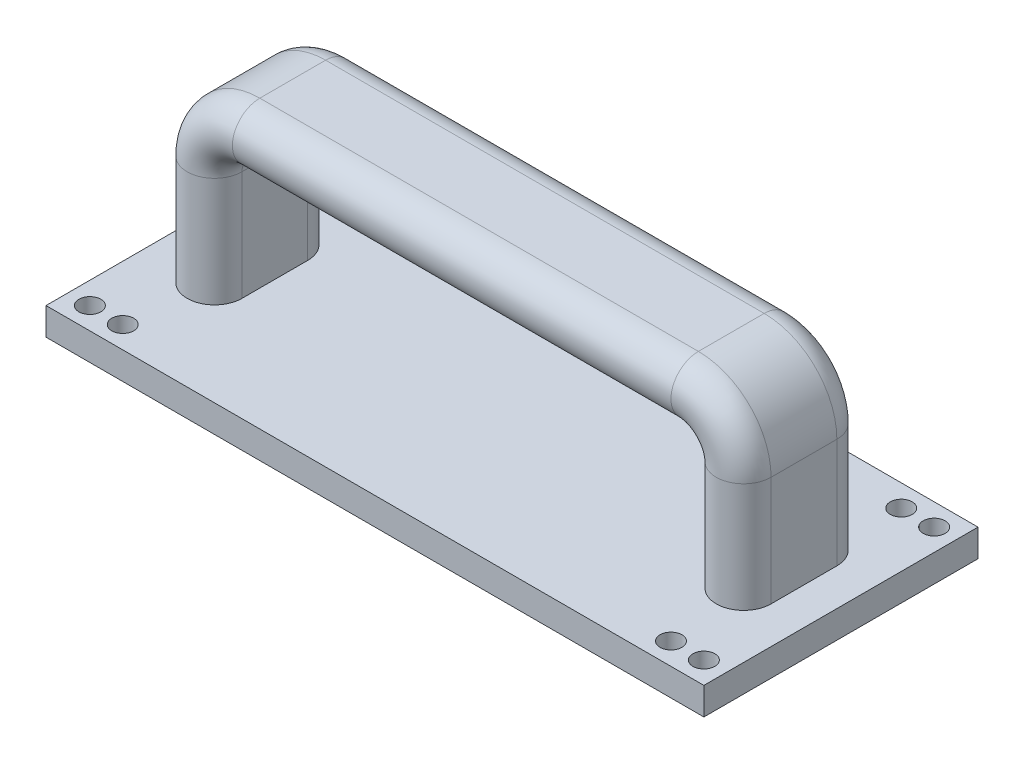
SolidWorks part; units mm, degrees
ref_plane "Front Plane" through (0, 0, 0) normal (0, 0, 1) x (1, 0, 0)
ref_plane "Top Plane" through (0, 0, 0) normal (0, 1, 0) x (1, 0, 0)
ref_plane "Right Plane" through (0, 0, 0) normal (1, 0, 0) x (0, 0, -1)
sketch "Sketch3" plane through (0, 0, 0) normal (0, 1, 0) x (1, 0, 0)
  line L1 (-60, -25) -> (60, -25)
  line L2 (-60, -25) -> (-60, 25)
  line L3 (-60, 25) -> (60, 25)
  line L4 (60, -25) -> (60, 25)
  line L5 (-60, -25) -> (60, 25) construction
  line L6 (-60, 25) -> (60, -25) construction
  point P0 (0, 0)
  dimension "D1" = 120
  dimension "D2" = 50
extrude "Boss-Extrude1" add sketch "Sketch3" along normal blind 5
sketch "Sketch4" plane through (0, 0, 0) normal (0, 0, 1) x (1, 0, 0)
  line L0 (-50, 5) -> (-50, 25)
  line L1 (-60, 5) -> (60, 5) construction
  line L2 (-40, 35) -> (40, 35)
  line L3 (0, 65.4422) -> (0, -12.7136) construction
  line L4 (50, 5) -> (50, 25)
  arc A0 (-50, 25) -> (-40, 35) centre (-40, 25) cw
  arc A1 (50, 25) -> (40, 35) centre (40, 25) ccw
  point P13 (0, 35)
  dimension "D1" = 10
  dimension "D2" = 30
  dimension "D3" = 100
sketch "Sketch5" plane through (0, 5, 0) normal (0, 1, 0) x (1, 0, 0)
  line L1 (-60, 0) -> (0, 0) construction
  line L3 (-60, 25) -> (-60, -25) construction
  line L4 (-40, 0) -> (40, 0) construction
  line L5 (-48.2577, 6) -> (-48.2577, -6) construction
  line L6 (-43.2577, 6) -> (-43.2577, -6)
  line L7 (-53.2577, 6) -> (-53.2577, -6)
  arc A1 (-43.2577, 6) -> (-53.2577, 6) centre (-48.2577, 6) ccw
  arc A2 (-53.2577, -6) -> (-43.2577, -6) centre (-48.2577, -6) ccw
  point P8 (-48.2577, 0)
  dimension "D1" = 10
sweep "Sweep1" add profiles "Sketch5" path "Sketch4"
sketch "Sketch6" plane through (0, 5, 0) normal (0, 1, 0) x (1, 0, 0)
  line L0 (60, 25) -> (-60, 25) construction
  line L1 (-60, 25) -> (-60, -25) construction
  line L2 (0, 0) -> (-60, 0) construction
  line L3 (0, 25) -> (0, -25) construction
  line L4 (-60, -25) -> (60, -25) construction
  circle A0 centre (-56, 21) radius 2
  circle A1 centre (-50, 21) radius 2
  circle A2 centre (-50, -21) radius 2
  circle A3 centre (-56, -21) radius 2
  circle A4 centre (56, -21) radius 2
  circle A5 centre (50, -21) radius 2
  circle A6 centre (50, 21) radius 2
  circle A7 centre (56, 21) radius 2
  dimension "D1" = 4
  dimension "D2" = 4
  dimension "D3" = 4
  dimension "D5" = 42
  dimension "D6" = 100
  dimension "D7" = 6
  dimension "D4" = 2
extrude "Cut-Extrude1" cut sketch "Sketch6" against normal blind 5
